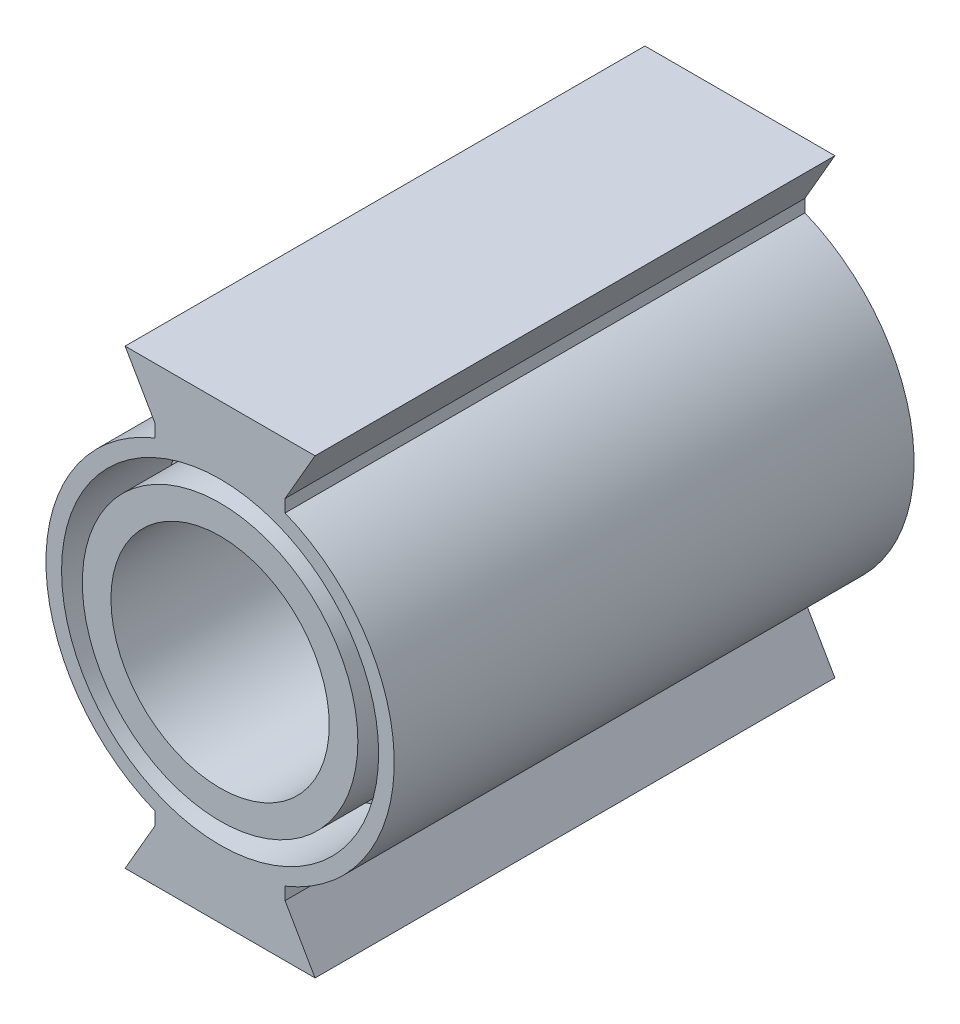
SolidWorks part; units mm, degrees
ref_plane "Front" through (0, 0, 0) normal (0, 0, 1) x (1, 0, 0)
ref_plane "Top" through (0, 0, 0) normal (0, 1, 0) x (1, 0, 0)
ref_plane "Right" through (0, 0, 0) normal (1, 0, 0) x (0, 0, -1)
sketch "Sketch1" plane through (0, 0, 0) normal (0, 0, 1) x (1, 0, 0)
  circle A0 centre (0, 0) radius 5.334
  circle A1 centre (0, 0) radius 8.509
  dimension "D1" = 10.668
  dimension "D2" = 17.018
extrude "Boss-Extrude1" add sketch "Sketch1" along normal blind 25.4
sketch "Sketch2" plane through (0, 0, 25.4) normal (0, 0, 1) x (1, 0, 0)
  circle A0 centre (0, 0) radius 6.731
  circle A1 centre (0, 0) radius 7.747
  dimension "D1" = 13.462
  dimension "D2" = 15.494
extrude "Cut-Extrude1" cut sketch "Sketch2" against normal blind 5.08
sketch "Sketch3" plane through (0, 0, 0) normal (0, 0, 1) x (1, 0, 0)
  line L4 (-3.175, 7.8945) -> (-3.175, 8.509)
  line L5 (3.175, 7.8945) -> (3.175, 8.509)
  line L6 (3.175, 8.509) -> (4.6415, 11.049)
  line L7 (4.6415, 11.049) -> (-4.6415, 11.049)
  line L8 (-4.6415, 11.049) -> (-3.175, 8.509)
  line L9 (-3.175, 8.509) -> (3.175, 8.509) construction
  circle A2 centre (0, 0) radius 8.509 construction
  arc A3 (-3.175, 7.8945) -> (3.175, 7.8945) centre (0, 0) cw
  point P10 (0, 8.509)
  dimension "D1" = 17.018
  dimension "D2" = 6.35
  dimension "D3" = 60
  dimension "D4" = 60
  dimension "D5" = 2.54
extrude "Boss-Extrude2" add sketch "Sketch3" along normal up to surface (25.4 mm away) up to face at (7.747, 0, 25.4)
mirror "Mirror1" about plane through (0, 0, 0) normal (0, 1, 0) of "Boss-Extrude2"
